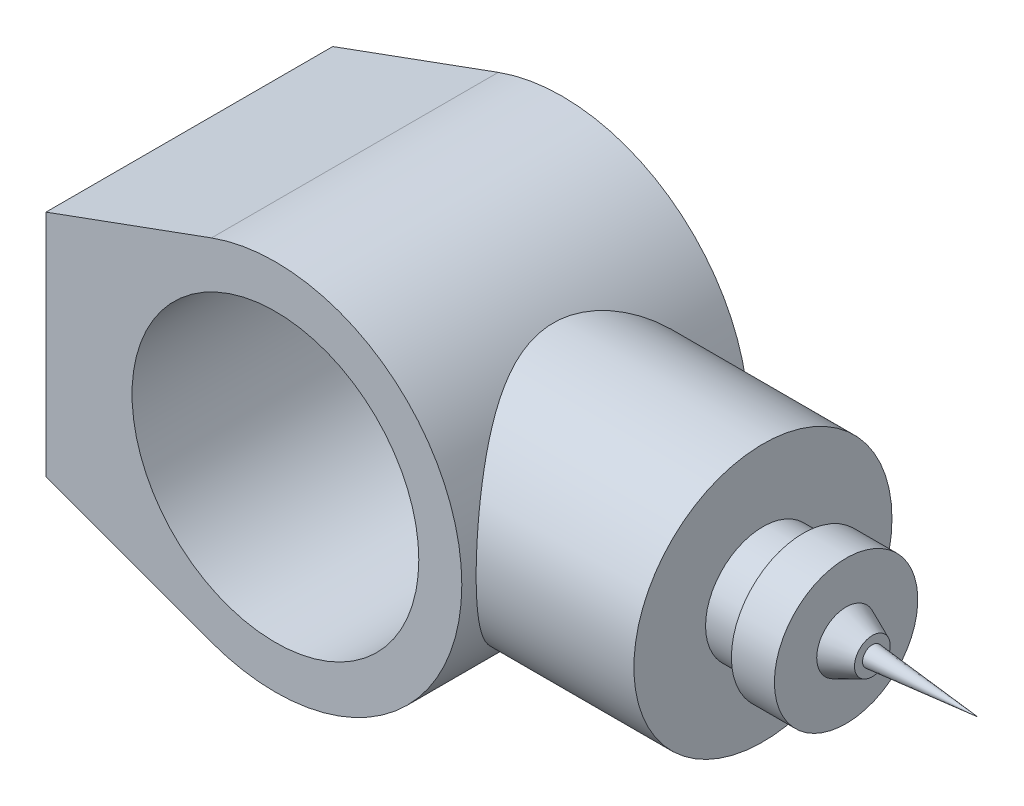
SolidWorks part; units mm, degrees
ref_plane "Front Plane" through (0, 0, 0) normal (0, 0, 1) x (1, 0, 0)
ref_plane "Top Plane" through (0, 0, 0) normal (0, 1, 0) x (1, 0, 0)
ref_plane "Right Plane" through (0, 0, 0) normal (1, 0, 0) x (0, 0, -1)
sketch "Sketch1" plane through (0, 0, 0) normal (0, 0, 1) x (1, 0, 0)
  line L0 (-80, -40) -> (-80, 40)
  line L1 (-80, 40) -> (-22.2817, 61.0617)
  line L2 (-80, -40) -> (-22.2817, -61.0617)
  circle A0 centre (0, 0) radius 50
  arc A1 (-22.2817, -61.0617) -> (-22.2817, 61.0617) centre (0, 0) ccw
  point P7 (-80, 0)
  dimension "D1" = 130
  dimension "D2" = 100
  dimension "D3" = 80
  dimension "D4" = 80
extrude "Boss-Extrude1" add sketch "Sketch1" along normal mid plane 100
ref_plane "Plane1" through (120, 0, 0) normal (1, 0, 0) x (0, 0, -1)
sketch "Sketch2" plane through (120, 0, 0) normal (1, 0, 0) x (0, 0, -1)
  circle A0 centre (0, 0) radius 45
  dimension "D1" = 90
extrude "Boss-Extrude2" add sketch "Sketch2" against normal up to next
sketch "Sketch3" plane through (0, 0, 0) normal (0, 0, 1) x (1, 0, 0)
  line L0 (0, 0) -> (231.4498, 0) construction
  line L1 (120, 0) -> (120, -20)
  line L2 (120, -45) -> (120, 45) construction
  line L3 (120, -20) -> (134, -20)
  line L4 (134, -20) -> (134, -25)
  line L5 (134, -25) -> (149, -25)
  line L6 (149, -25) -> (149, -10.2436)
  line L7 (149, -10.2436) -> (158.1585, -6.2283)
  line L8 (158.1585, -6.2283) -> (158.1585, -3.4207)
  line L9 (158.1585, -3.4207) -> (195, 0)
  line L10 (120, 0) -> (195, 0)
  dimension "D1" = 20
  dimension "D2" = 14
  dimension "D3" = 15
  dimension "D4" = 5
  dimension "D5" = 37
  dimension "D6" = 10
  dimension "D7" = 75
revolve "Revolve1" add sketch "Sketch3" angle 360 about L0
